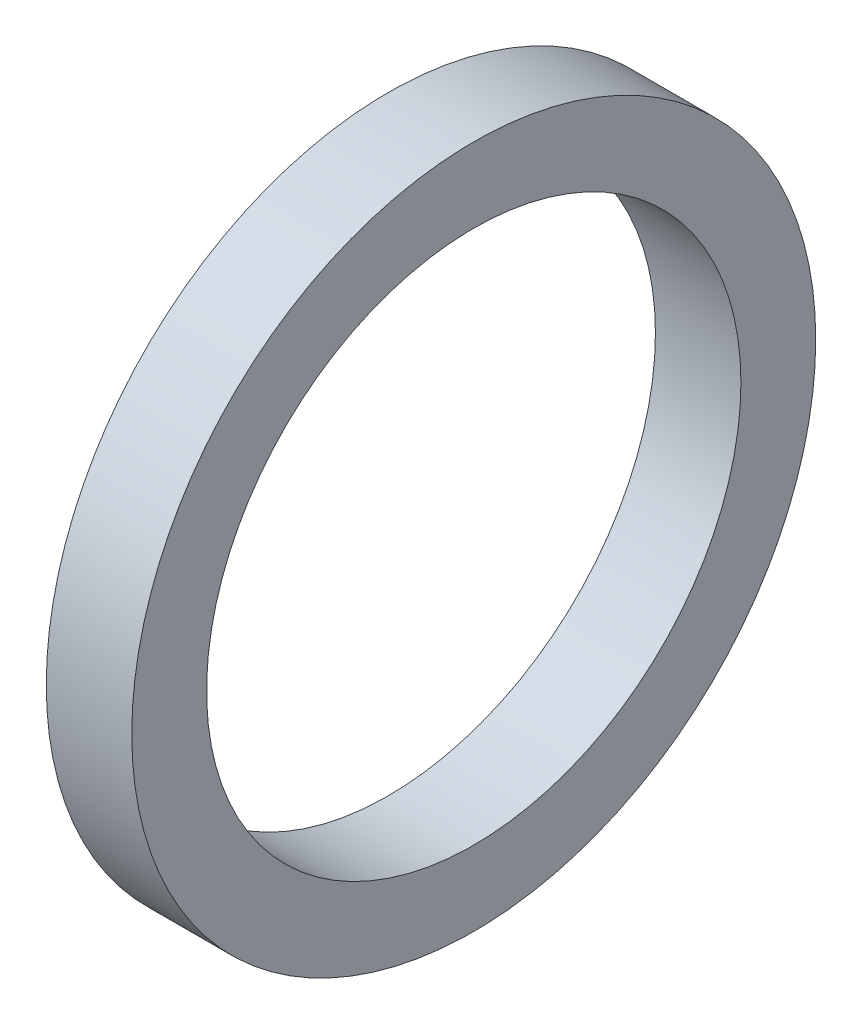
SolidWorks part; units mm, degrees
material "AISI 304"
ref_plane "前视基准面" through (0, 0, 0) normal (0, 0, 1) x (1, 0, 0)
ref_plane "上视基准面" through (0, 0, 0) normal (0, 1, 0) x (1, 0, 0)
ref_plane "右视基准面" through (0, 0, 0) normal (1, 0, 0) x (0, 0, -1)
sketch "草图1" plane through (0, 0, 0) normal (1, 0, 0) x (0, 0, -1)
  circle A0 centre (0, 0) radius 12.5
  circle A1 centre (0, 0) radius 16
  dimension "D1" = 32
  dimension "D2" = 25
extrude "凸台-拉伸1" add sketch "草图1" along normal blind 4
